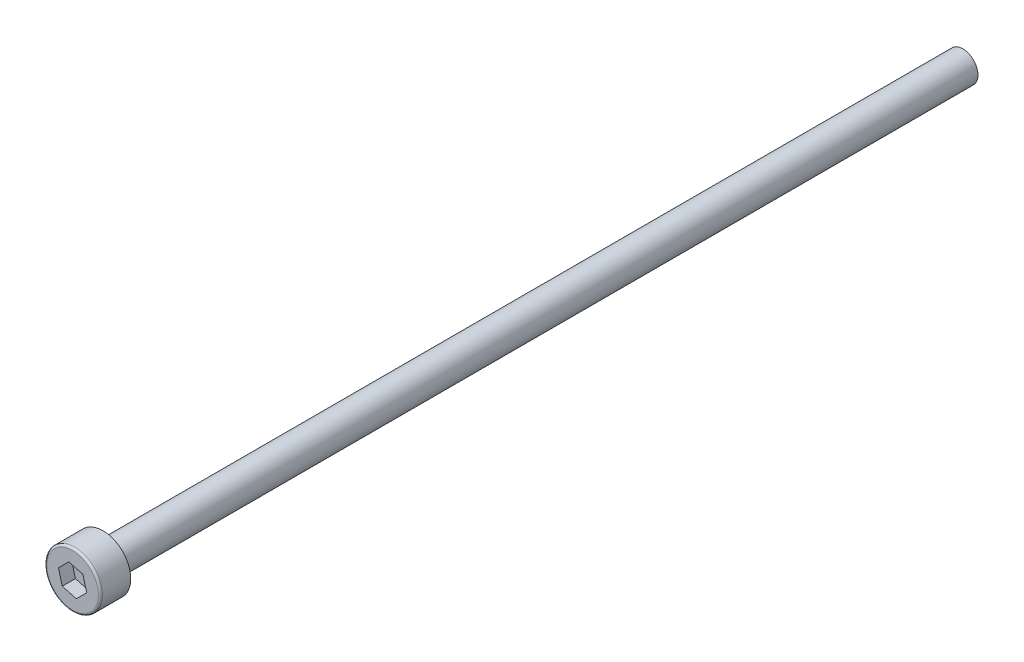
SolidWorks part; units mm, degrees
ref_plane "前视基准面" through (0, 0, 0) normal (0, 0, 1) x (1, 0, 0)
ref_plane "上视基准面" through (0, 0, 0) normal (0, 1, 0) x (1, 0, 0)
ref_plane "右视基准面" through (0, 0, 0) normal (1, 0, 0) x (0, 0, -1)
sketch "草图1" plane through (0, 0, 0) normal (0, 0, 1) x (1, 0, 0)
  circle A0 centre (0, 0) radius 2.75
  dimension "D1" = 5.5
extrude "凸台-拉伸1" add sketch "草图1" along normal blind 3
sketch "草图2" plane through (0, 0, 3) normal (0, 0, 1) x (1, 0, 0)
  line L1 (-1.0206, -1.0206) -> (0.3736, -1.3942)
  line L2 (0.3736, -1.3942) -> (1.3942, -0.3736)
  line L3 (1.3942, -0.3736) -> (1.0206, 1.0206)
  line L4 (1.0206, 1.0206) -> (-0.3736, 1.3942)
  line L5 (-0.3736, 1.3942) -> (-1.3942, 0.3736)
  line L6 (-1.3942, 0.3736) -> (-1.0206, -1.0206)
  circle A0 centre (0, 0) radius 1.25 construction
  dimension "D1" = 2.5
extrude "切除-拉伸1" cut sketch "草图2" against normal blind 1.3
sketch "草图3" plane through (0, 0, 0) normal (0, 0, -1) x (-1, 0, 0)
  circle A0 centre (0, 0) radius 1.5
  dimension "D1" = 3
extrude "凸台-拉伸2" add sketch "草图3" along normal blind 85
fillet "圆角1" radius 0.2 1 edges at (2.75, 0, 3)
